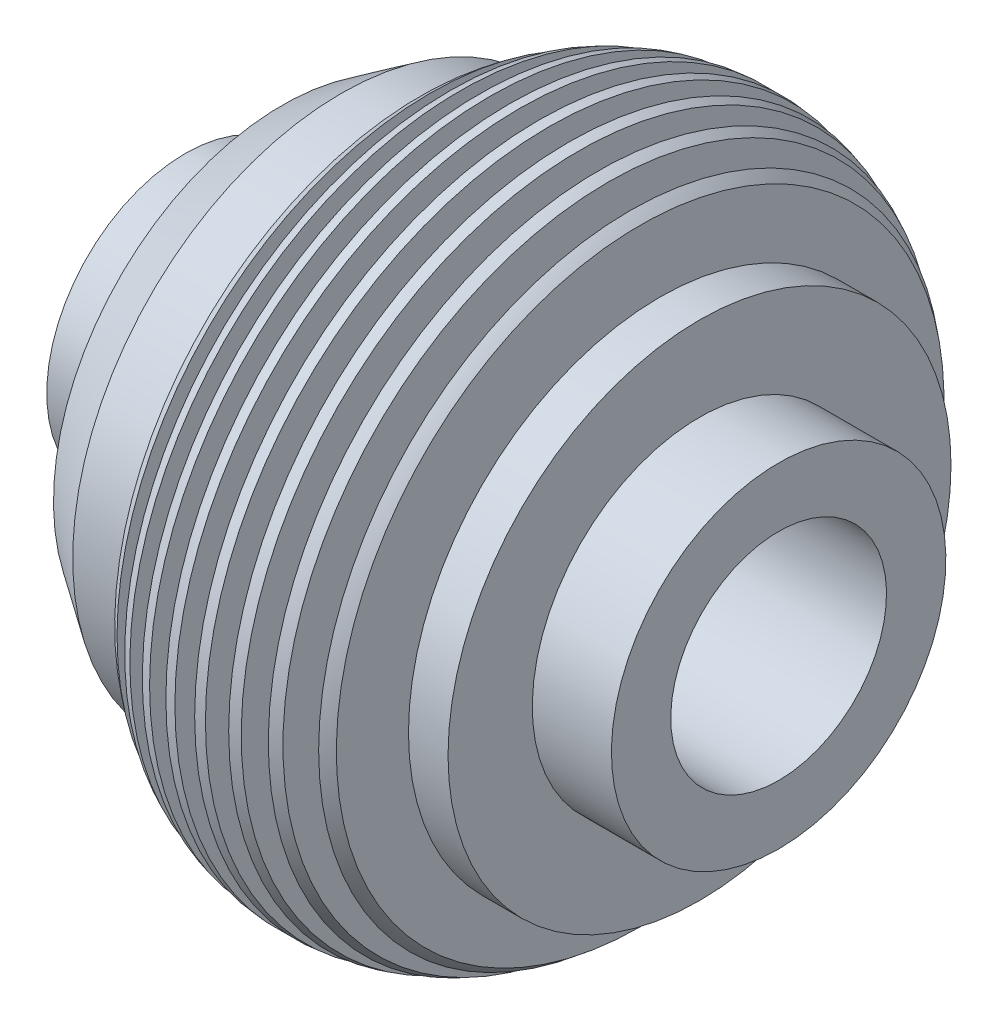
SolidWorks part; units mm, degrees
ref_plane "Front Plane" through (0, 0, 0) normal (0, 0, 1) x (1, 0, 0)
ref_plane "Top Plane" through (0, 0, 0) normal (0, 1, 0) x (1, 0, 0)
ref_plane "Right Plane" through (0, 0, 0) normal (1, 0, 0) x (0, 0, -1)
sketch "Sketch1" plane through (0, 0, 0) normal (0, 0, 1) x (1, 0, 0)
  line L0 (-50, 20) -> (-50, 0)
  line L1 (-50, 0) -> (0, 0)
  line L2 (0, 0) -> (0, 12.2699)
  line L6 (26.9391, 28.8266) -> (26.9391, 70.9561)
  line L8 (24.4391, 70.2831) -> (24.4391, 28.8266)
  line L9 (24.4391, 28.8266) -> (19.4391, 28.8266)
  line L10 (19.4391, 28.8266) -> (19.4391, 68.4327)
  line L12 (16.9391, 67.2309) -> (16.9391, 28.8266)
  line L13 (16.9391, 28.8266) -> (11.9391, 28.8266)
  line L14 (11.9391, 28.8266) -> (11.9391, 64.1804)
  line L16 (9.4391, 62.2727) -> (9.4391, 28.8266)
  line L17 (9.4391, 28.8266) -> (4.4391, 28.8266)
  line L18 (4.4391, 28.8266) -> (4.4391, 52.8835)
  line L19 (4.4391, 52.8835) -> (-10.5609, 52.8835)
  line L20 (-10.5609, 52.8835) -> (-25.4836, 42.818)
  line L21 (-25.4836, 42.818) -> (-25.4836, 26.1938)
  line L22 (-25.4836, 21.1938) -> (-25.4836, 20)
  line L23 (-35.4836, 10) -> (-40, 10)
  line L24 (-40, 10) -> (-40, 20)
  line L25 (-40, 20) -> (-50, 20)
  line L26 (26.9391, 28.8266) -> (31.9391, 28.8266)
  line L27 (31.9391, 28.8266) -> (31.9391, 71.837)
  line L29 (34.4391, 72.0544) -> (34.4391, 28.8266)
  line L30 (34.4391, 28.8266) -> (39.4391, 28.8266)
  line L31 (39.4391, 28.8266) -> (39.4391, 72.0544)
  line L33 (41.9391, 71.837) -> (41.9391, 28.8266)
  line L34 (41.9391, 28.8266) -> (46.9391, 28.8266)
  line L35 (46.9391, 28.8266) -> (46.9391, 70.9561)
  line L37 (49.4391, 70.2831) -> (49.4391, 28.8266)
  line L38 (49.4391, 28.8266) -> (54.4391, 28.8266)
  line L39 (54.4391, 28.8266) -> (54.4391, 68.4327)
  line L41 (56.9391, 67.2309) -> (56.9391, 28.8266)
  line L42 (56.9391, 28.8266) -> (62.5, 28.8266)
  line L43 (62.5, 28.8266) -> (62.5, 63.777)
  line L45 (65, 61.8035) -> (65, 28.8266)
  line L46 (65, 28.8266) -> (70, 28.8266)
  line L47 (70, 28.8266) -> (70, 48.5699)
  line L48 (70, 48.5699) -> (80, 48.5699)
  line L50 (80, 48.5699) -> (80, 27.2699)
  line L51 (80, 27.2699) -> (100, 27.2699)
  line L52 (100, 27.2699) -> (100, 12.2699)
  line L54 (36.9391, 28.8266) -> (36.9391, 2.287) construction
  line L55 (29.4391, 28.8266) -> (29.4391, 12.2699)
  line L56 (44.4391, 28.8266) -> (44.4391, 12.2699)
  line L57 (0, 12.2699) -> (100, 12.2699)
  line L63 (-50, -15) -> (113.1691, -15) construction
  line L64 (29.4391, 12.2699) -> (44.4391, 12.2699)
  line L65 (-25.4836, 21.518) -> (-25.4836, 21.1938)
  line L66 (-25.4836, 26.1938) -> (-25.4836, 21.518)
  arc A1 (65, 61.8035) -> (62.5, 63.777) centre (36.9391, 28.8266) ccw
  arc A2 (11.9391, 64.1804) -> (9.4391, 62.2727) centre (36.9391, 28.8266) ccw
  arc A3 (19.4391, 68.4327) -> (16.9391, 67.2309) centre (36.9391, 28.8266) ccw
  arc A4 (26.9391, 70.9561) -> (24.4391, 70.2831) centre (36.9391, 28.8266) ccw
  arc A5 (34.4391, 72.0544) -> (31.9391, 71.837) centre (36.9391, 28.8266) ccw
  arc A6 (41.9391, 71.837) -> (39.4391, 72.0544) centre (36.9391, 28.8266) ccw
  arc A7 (49.4391, 70.2831) -> (46.9391, 70.9561) centre (36.9391, 28.8266) ccw
  arc A8 (56.9391, 67.2309) -> (54.4391, 68.4327) centre (36.9391, 28.8266) ccw
  arc A9 (-25.4836, 20) -> (-35.4836, 10) centre (-35.4836, 20) cw
  dimension "D31" = 51.9105
  dimension "D20" = 10
  dimension "D22" = 43.3
  dimension "D24" = 15
  dimension "D25" = 16.5567
  dimension "D28" = 28.8266
  dimension "D33" = 24.0569
  dimension "D35" = 35.4836
  dimension "D1" = 50
  dimension "D2" = 20
  dimension "D3" = 10
  dimension "D4" = 21.3
  dimension "D5" = 18
  dimension "D6" = 15
  dimension "D7" = 10
  dimension "D8" = 146
  dimension "D9" = 5
  dimension "D10" = 5
  dimension "D11" = 5
  dimension "D12" = 100
  dimension "D13" = 5
  dimension "D14" = 5
  dimension "D15" = 5
  dimension "D16" = 5
  dimension "D17" = 5.5609
  dimension "D18" = 5
  dimension "D19" = 15
  dimension "D23" = 2.5
  dimension "D27" = 10
  dimension "D29" = 15
  dimension "D30" = 20
  dimension "D32" = 36.9391
  dimension "D36" = 36.3
  dimension "D37" = 68.4327
  dimension "D38" = 70.9561
revolve "Revolve1" add sketch "Sketch1" angle 360 about L63
